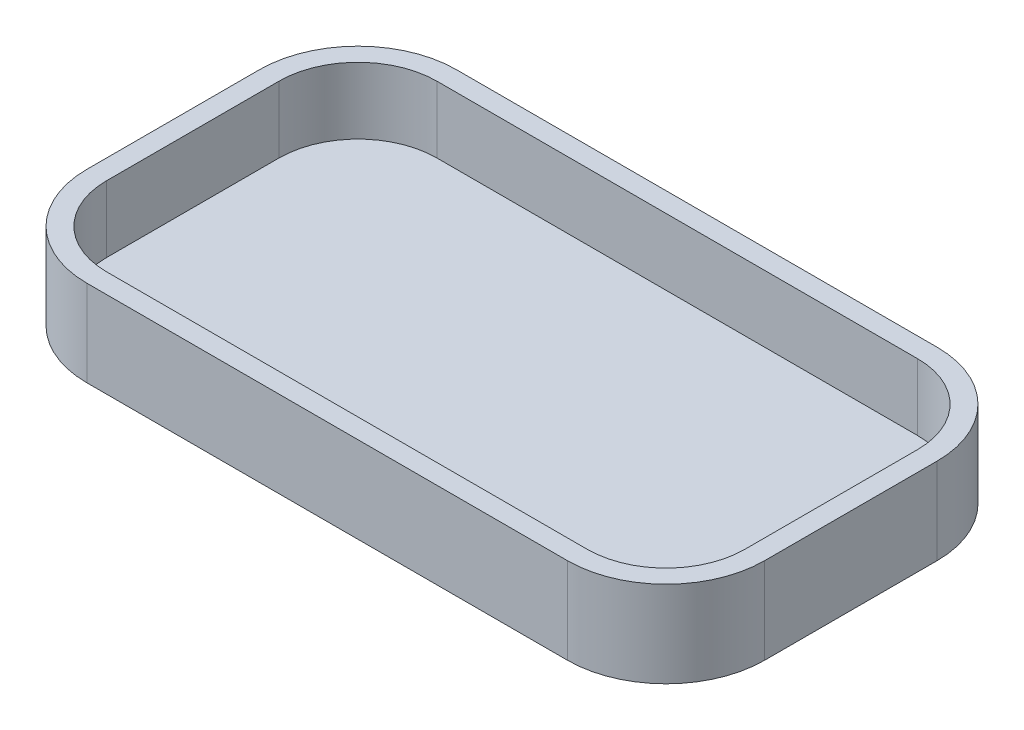
SolidWorks part; units mm, degrees
material "ABS"
ref_plane "Front Plane" through (0, 0, 0) normal (0, 0, 1) x (1, 0, 0)
ref_plane "Top Plane" through (0, 0, 0) normal (0, 1, 0) x (1, 0, 0)
ref_plane "Right Plane" through (0, 0, 0) normal (1, 0, 0) x (0, 0, -1)
sketch "Sketch1" plane through (0, 0, 0) normal (0, 1, 0) x (1, 0, 0)
  line L1 (-27.5, -15) -> (27.5, -15)
  line L2 (-27.5, -15) -> (-27.5, 15)
  line L3 (-27.5, 15) -> (27.5, 15)
  line L4 (27.5, -15) -> (27.5, 15)
  line L5 (-27.5, -15) -> (27.5, 15) construction
  line L6 (-27.5, 15) -> (27.5, -15) construction
  point P0 (0, 0)
  dimension "D1" = 55
  dimension "D2" = 30
extrude "Boss-Extrude1" add sketch "Sketch1" along normal blind 7
fillet "Fillet1" radius 8 4 edges at (-27.5, 3.5, -15) (27.5, 3.5, -15) (27.5, 3.5, 15) (-27.5, 3.5, 15)
shell "Shell1" thickness 1.6
